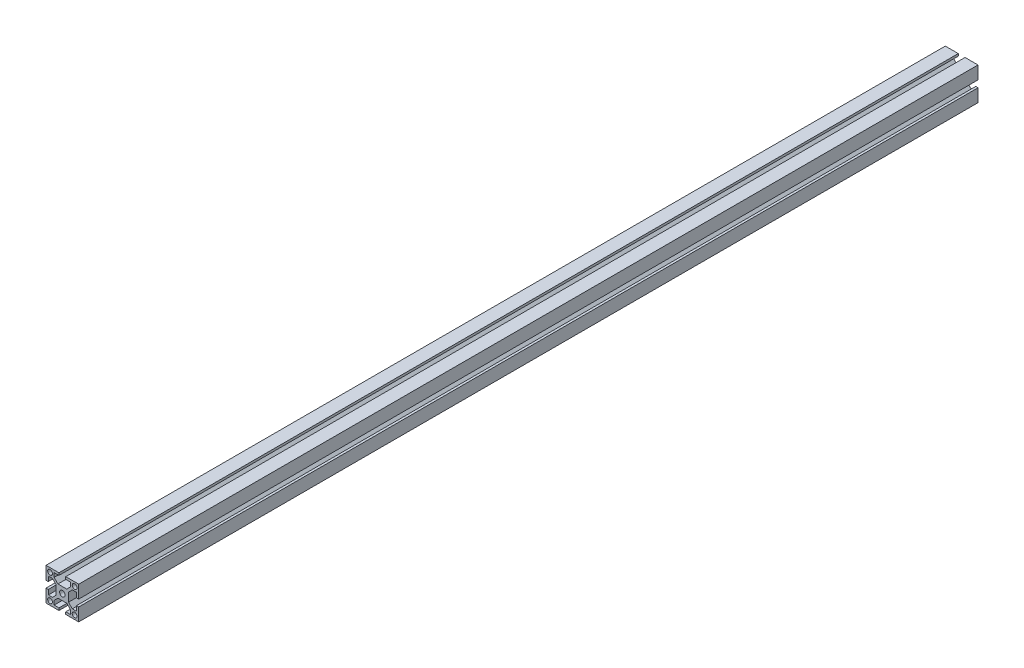
SolidWorks part; units mm, degrees
ref_plane "前视基准面" through (0, 0, 0) normal (0, 0, 1) x (1, 0, 0)
ref_plane "上视基准面" through (0, 0, 0) normal (0, 1, 0) x (1, 0, 0)
ref_plane "右视基准面" through (0, 0, 0) normal (1, 0, 0) x (0, 0, -1)
sketch "草图1" plane through (0, 0, 0) normal (0, 0, 1) x (1, 0, 0)
  line L0 (-13.7081, 1.927) -> (23.4501, 39.0852) construction
  line L1 (-19.0867, -5.573) -> (-8.3294, -5.573)
  line L2 (-21.2081, -3.4517) -> (-21.2081, 7.3057)
  line L3 (-19.0867, 9.427) -> (-8.3294, 9.427)
  line L4 (-6.2081, -3.4517) -> (-6.2081, 7.3057)
  line L5 (-21.2081, -5.573) -> (-6.2081, 9.427) construction
  line L6 (-21.2081, 9.427) -> (-6.2081, -5.573) construction
  line L7 (-6.2081, 7.3057) -> (-1.5367, 11.977)
  line L8 (6.2919, 21.927) -> (6.2919, 6.077)
  line L9 (6.2919, 21.927) -> (-9.5581, 21.927)
  line L10 (6.2919, 6.077) -> (3.4919, 6.077)
  line L11 (-9.5581, 21.927) -> (-9.5581, 19.127)
  line L12 (3.4919, 6.077) -> (3.4919, 11.977)
  line L13 (-1.5367, 11.977) -> (3.4919, 11.977)
  line L14 (-9.5581, 19.127) -> (-3.6581, 19.127)
  line L15 (-3.6581, 14.0983) -> (-3.6581, 19.127)
  line L16 (-8.3294, 9.427) -> (-3.6581, 14.0983)
  line L17 (-19.0867, 9.427) -> (-23.7581, 14.0983)
  line L18 (-23.7581, 14.0983) -> (-23.7581, 19.127)
  line L19 (-17.8581, 19.127) -> (-23.7581, 19.127)
  line L20 (-25.8794, 11.977) -> (-30.9081, 11.977)
  line L21 (-30.9081, 6.077) -> (-30.9081, 11.977)
  line L22 (-17.8581, 21.927) -> (-17.8581, 19.127)
  line L23 (-33.7081, 6.077) -> (-30.9081, 6.077)
  line L24 (-33.7081, 21.927) -> (-17.8581, 21.927)
  line L25 (-33.7081, 21.927) -> (-33.7081, 6.077)
  line L26 (-21.2081, 7.3057) -> (-25.8794, 11.977)
  line L27 (-21.2081, -3.4517) -> (-25.8794, -8.123)
  line L28 (-33.7081, -18.073) -> (-33.7081, -2.223)
  line L29 (-33.7081, -18.073) -> (-17.8581, -18.073)
  line L30 (-33.7081, -2.223) -> (-30.9081, -2.223)
  line L31 (-17.8581, -18.073) -> (-17.8581, -15.273)
  line L32 (-30.9081, -2.223) -> (-30.9081, -8.123)
  line L33 (-25.8794, -8.123) -> (-30.9081, -8.123)
  line L34 (-17.8581, -15.273) -> (-23.7581, -15.273)
  line L35 (-23.7581, -10.2443) -> (-23.7581, -15.273)
  line L36 (-19.0867, -5.573) -> (-23.7581, -10.2443)
  line L37 (-8.3294, -5.573) -> (-3.6581, -10.2443)
  line L38 (-3.6581, -10.2443) -> (-3.6581, -15.273)
  line L39 (-9.5581, -15.273) -> (-3.6581, -15.273)
  line L40 (-1.5367, -8.123) -> (3.4919, -8.123)
  line L41 (3.4919, -2.223) -> (3.4919, -8.123)
  line L42 (-9.5581, -18.073) -> (-9.5581, -15.273)
  line L43 (6.2919, -2.223) -> (3.4919, -2.223)
  line L44 (6.2919, -18.073) -> (-9.5581, -18.073)
  line L45 (6.2919, -18.073) -> (6.2919, -2.223)
  line L46 (-6.2081, -3.4517) -> (-1.5367, -8.123)
  circle A0 centre (-13.7081, 1.927) radius 3.4
  circle A1 centre (1.3169, 16.952) radius 2.95
  circle A2 centre (-28.7331, 16.952) radius 2.95
  circle A3 centre (-28.7331, -13.098) radius 2.95
  circle A4 centre (1.3169, -13.098) radius 2.95
  dimension "D1" = 6.8
  dimension "D4" = 5.9
  dimension "D2" = 15
  dimension "D3" = 15
  dimension "D5" = 2.8
  dimension "D6" = 7.5
  dimension "D7" = 3
extrude "凸台-拉伸1" add sketch "草图1" along normal blind 1100
